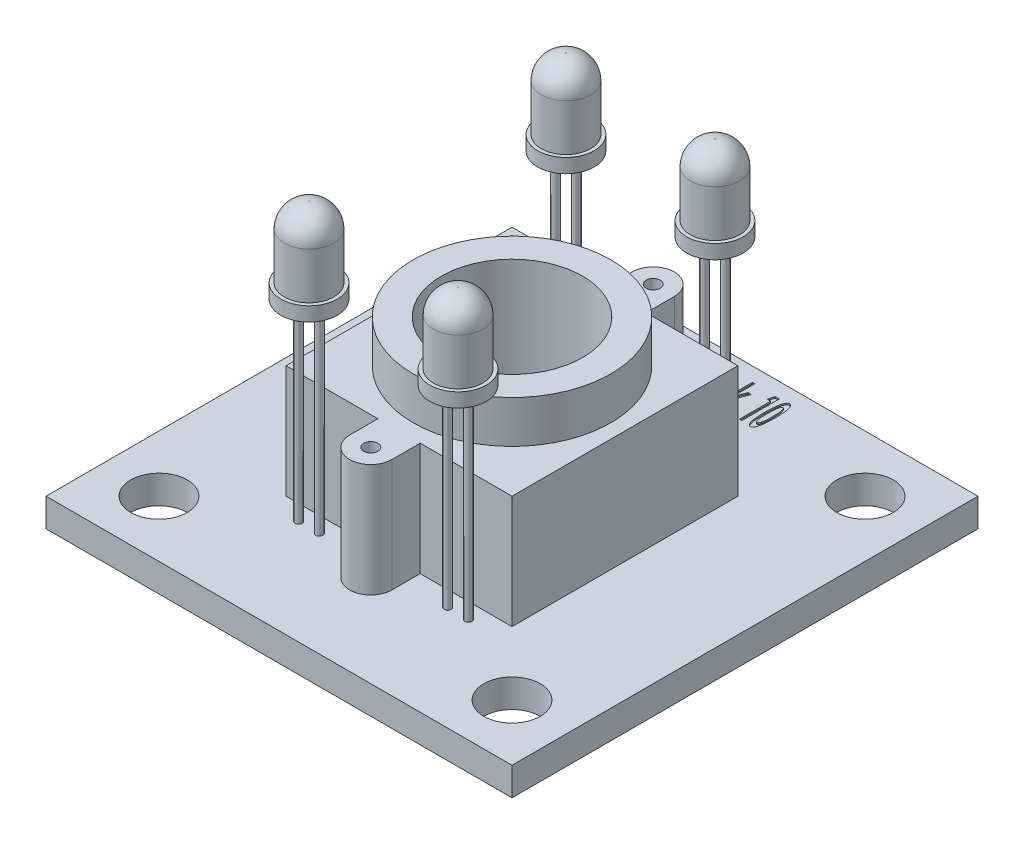
SolidWorks part; units mm, degrees
ref_plane "Front Plane" through (0, 0, 0) normal (0, 0, 1) x (1, 0, 0)
ref_plane "Top Plane" through (0, 0, 0) normal (0, 1, 0) x (1, 0, 0)
ref_plane "Right Plane" through (0, 0, 0) normal (1, 0, 0) x (0, 0, -1)
sketch "Sketch1" plane through (0, 0, 0) normal (0, 1, 0) x (1, 0, 0)
  line L0 (-36.0416, 40.1803) -> (-3.0416, 7.1803) construction
  line L1 (-36.0416, 40.1803) -> (-3.0416, 40.1803)
  line L2 (-36.0416, 40.1803) -> (-36.0416, 7.1803)
  line L3 (-36.0416, 7.1803) -> (-3.0416, 7.1803)
  line L4 (-3.0416, 40.1803) -> (-3.0416, 7.1803)
  line L5 (-3.0416, 40.1803) -> (-36.0416, 7.1803) construction
  dimension "D1" = 33
  dimension "D2" = 33
extrude "Boss-Extrude1" add sketch "Sketch1" along normal blind 2
sketch "Sketch2" plane through (0, 2, 0) normal (0, 1, 0) x (1, 0, 0)
  line L1 (-3.0416, 40.1803) -> (-36.0416, 40.1803) construction
  circle A0 centre (-32.0416, 36.1803) radius 2
  circle A1 centre (-7.0416, 36.1803) radius 2
  circle A2 centre (-7.0416, 11.1803) radius 2
  circle A3 centre (-32.0416, 11.1803) radius 2
  dimension "D5" = 4
  dimension "D6" = 4
  dimension "D7" = 4
  dimension "D8" = 4
  dimension "D1" = 4
  dimension "D2" = 4
  dimension "D3" = 4
  dimension "D4" = 4
  dimension "D9" = 4
  dimension "D10" = 4
  dimension "D11" = 4
  dimension "D12" = 4
extrude "Cut-Extrude1" cut sketch "Sketch2" against normal blind 2
sketch "Sketch7" plane through (0, 2, 0) normal (0, 1, 0) x (1, 0, 0)
  line L0 (-36.0416, 40.1803) -> (-3.0416, 7.1803) construction
  line L1 (-3.0416, 40.1803) -> (-36.0416, 7.1803) construction
  line L2 (-21.0416, 15.6803) -> (-21.0416, 13.6803)
  line L3 (-27.5416, 31.6803) -> (-21.0416, 31.6803)
  line L4 (-27.5416, 31.6803) -> (-27.5416, 15.6803)
  line L5 (-27.5416, 15.6803) -> (-21.0416, 15.6803)
  line L6 (-11.5416, 31.6803) -> (-11.5416, 15.6803)
  line L7 (-18.0416, 15.6803) -> (-18.0416, 13.6803)
  line L8 (-18.0416, 33.6803) -> (-18.0416, 31.6803)
  line L9 (-21.0416, 33.6803) -> (-21.0416, 31.6803)
  line L10 (-18.0416, 31.6803) -> (-11.5416, 31.6803)
  line L11 (-18.0416, 15.6803) -> (-11.5416, 15.6803)
  arc A0 (-18.0416, 33.6803) -> (-21.0416, 33.6803) centre (-19.5416, 33.6803) ccw
  arc A1 (-21.0416, 13.6803) -> (-18.0416, 13.6803) centre (-19.5416, 13.6803) ccw
  point P12 (-19.5416, 23.6803)
  point P13 (-19.5416, 23.6803)
  dimension "D6" = 1.5
  dimension "D1" = 8
  dimension "D2" = 8
  dimension "D3" = 8
  dimension "D4" = 2
  dimension "D5" = 2
extrude "Boss-Extrude2" add sketch "Sketch7" along normal blind 8
sketch "Sketch8" plane through (0, 10, 0) normal (0, 1, 0) x (1, 0, 0)
  circle A0 centre (-19.5416, 33.6803) radius 0.5
  circle A1 centre (-19.5416, 13.6803) radius 0.5
  dimension "D1" = 1
  dimension "D2" = 1
extrude "Cut-Extrude2" cut sketch "Sketch8" against normal blind 5
sketch "Sketch9" plane through (0, 2, 0) normal (0, 1, 0) x (1, 0, 0)
  circle A0 centre (-25.5514, 32.7772) radius 0.25
  circle A1 centre (-24.0846, 32.7772) radius 0.25
  circle A3 centre (-14.9987, 32.7772) radius 0.25
  circle A4 centre (-13.5318, 32.7772) radius 0.25
  circle A6 centre (-24.0846, 14.5833) radius 0.25
  circle A7 centre (-25.5514, 14.5833) radius 0.25
  circle A8 centre (-14.9987, 14.5833) radius 0.25
  circle A9 centre (-13.5318, 14.5833) radius 0.25
  dimension "D1" = 0.5
  dimension "D2" = 0.5
extrude "Boss-Extrude3" add sketch "Sketch9" along normal blind 14
sketch "Sketch13" plane through (0, 16, 0) normal (0, 1, 0) x (1, 0, 0)
  circle A0 centre (-14.2653, 14.5833) radius 2
  circle A1 centre (-24.818, 32.7772) radius 2
  circle A2 centre (-24.818, 14.5833) radius 2
  circle A3 centre (-14.2653, 32.7772) radius 2
  dimension "D1" = 4
  dimension "D2" = 4
  dimension "D3" = 4
  dimension "D4" = 4
extrude "Boss-Extrude6" add sketch "Sketch13" along normal blind 1
sketch "Sketch25" plane through (0, 17, 0) normal (0, 1, 0) x (1, 0, 0)
  line L0 (-24.818, 34.7772) -> (-24.818, 30.7772) construction
  circle A0 centre (-24.818, 32.7772) radius 2 construction
  circle A1 centre (-24.818, 32.7772) radius 1.75
  dimension "D1" = 3.5
extrude "Boss-Extrude7" add sketch "Sketch25" along normal blind 5
fillet "Fillet4" radius 1.7 1 edges at (-24.818, 22, -31.0272)
sketch "Sketch26" plane through (0, 17, 0) normal (0, 1, 0) x (1, 0, 0)
  line L0 (-14.2653, 34.7772) -> (-14.2653, 30.7772) construction
  circle A0 centre (-14.2653, 32.7772) radius 2 construction
  circle A1 centre (-14.2653, 32.7772) radius 1.75
  dimension "D1" = 3.5
extrude "Boss-Extrude8" add sketch "Sketch26" along normal blind 5
fillet "Fillet5" radius 1.7 1 edges at (-14.2653, 22, -31.0272)
sketch "Sketch27" plane through (0, 17, 0) normal (0, 1, 0) x (1, 0, 0)
  line L0 (-24.818, 16.5833) -> (-24.818, 12.5833) construction
  circle A0 centre (-24.818, 14.5833) radius 2 construction
  circle A1 centre (-24.818, 14.5833) radius 1.75
  dimension "D1" = 3.5
extrude "Boss-Extrude9" add sketch "Sketch27" along normal blind 5
fillet "Fillet6" radius 1.7 1 edges at (-24.818, 22, -12.8333)
sketch "Sketch28" plane through (0, 17, 0) normal (0, 1, 0) x (1, 0, 0)
  line L0 (-14.2653, 16.5833) -> (-14.2653, 12.5833) construction
  circle A0 centre (-14.2653, 14.5833) radius 2 construction
  circle A1 centre (-14.2653, 14.5833) radius 1.75
  dimension "D1" = 3.5
extrude "Boss-Extrude10" add sketch "Sketch28" along normal blind 5
fillet "Fillet7" radius 1.7 1 edges at (-14.2653, 22, -12.8333)
sketch "Sketch29" plane through (0, 10, 0) normal (0, 1, 0) x (1, 0, 0)
  line L0 (-27.5416, 31.6803) -> (-11.5416, 15.6803) construction
  line L1 (-27.5416, 23.6803) -> (-11.5416, 23.6803) construction
  line L2 (-27.5416, 31.6803) -> (-27.5416, 15.6803) construction
  line L3 (-11.5416, 15.6803) -> (-11.5416, 31.6803) construction
  circle A0 centre (-19.5416, 23.6803) radius 7
  dimension "D1" = 14
extrude "Boss-Extrude11" add sketch "Sketch29" along normal blind 3
sketch "Sketch30" plane through (0, 13, 0) normal (0, 1, 0) x (1, 0, 0)
  circle A0 centre (-19.5416, 23.6803) radius 5
  circle A1 centre (-19.5416, 23.6803) radius 7 construction
  dimension "D1" = 2
extrude "Cut-Extrude4" cut sketch "Sketch30" against normal blind 9
sketch "Sketch31" plane through (0, 2, 0) normal (0, 1, 0) x (1, 0, 0)
  text T0 "<b>kelompok_10</b>" font "Century Gothic" height in points 10
extrude "Cut-Extrude5" cut sketch "Sketch31" against normal blind 0.1
